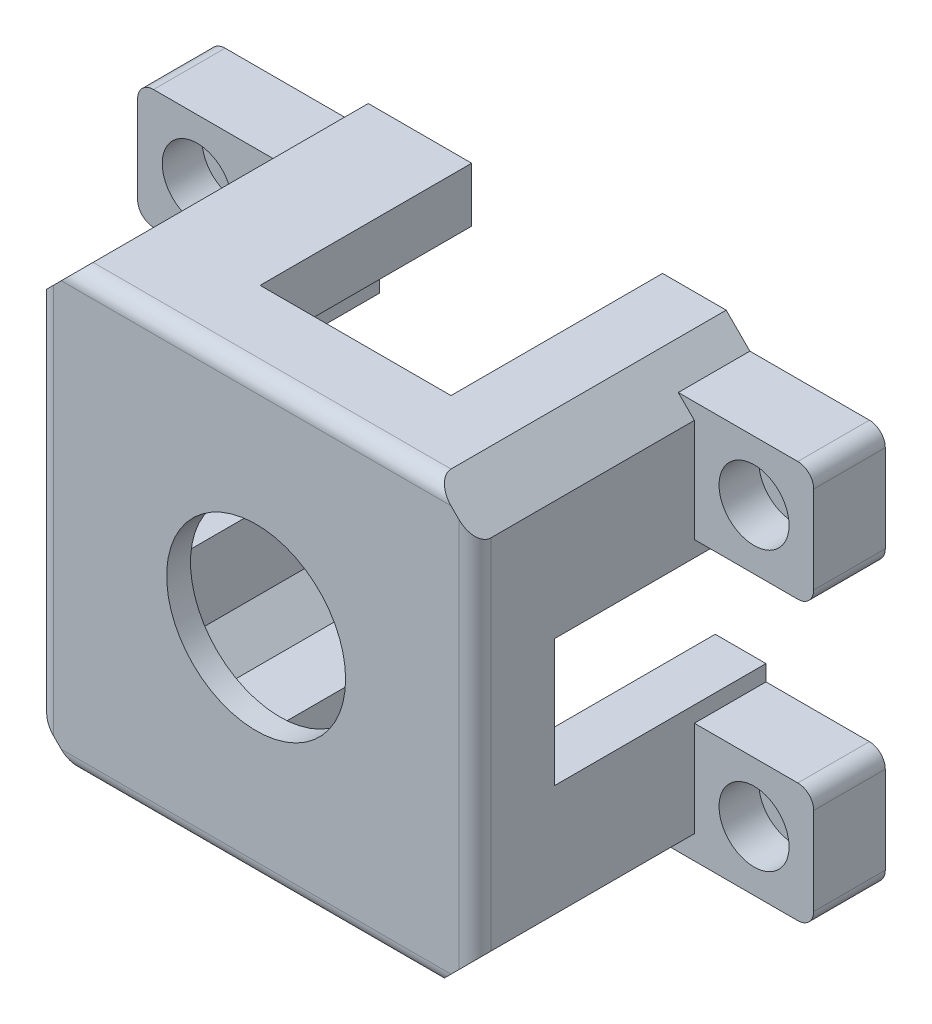
SolidWorks part; units mm, degrees
ref_plane "Front Plane" through (0, 0, 0) normal (0, 0, 1) x (1, 0, 0)
ref_plane "Top Plane" through (0, 0, 0) normal (0, 1, 0) x (1, 0, 0)
ref_plane "Right Plane" through (0, 0, 0) normal (1, 0, 0) x (0, 0, -1)
sketch "Sketch2" plane through (0, 0, 0) normal (0, 0, 1) x (1, 0, 0)
  line L1 (-27.5, -27.0238) -> (27.5, -27.0238)
  line L2 (-27.5, -27.0238) -> (-27.5, 27.9762)
  line L3 (-27.5, 27.9762) -> (27.5, 27.9762)
  line L4 (27.5, -27.0238) -> (27.5, 27.9762)
  line L5 (-27.5, -27.0238) -> (27.5, 27.9762) construction
  line L6 (-27.5, 27.9762) -> (27.5, -27.0238) construction
  line L16 (21.1184, 17.2806) -> (17.2806, 21.1184)
  line L17 (17.2806, 21.1184) -> (-17.2806, 21.1184)
  line L18 (-17.2806, 21.1184) -> (-21.1184, 17.2806)
  line L19 (-21.1184, 17.2806) -> (-21.1184, -17.2806)
  line L20 (-21.1184, -17.2806) -> (-17.2806, -21.1184)
  line L21 (-17.2806, -21.1184) -> (17.2806, -21.1184)
  line L22 (17.2806, -21.1184) -> (21.1184, -17.2806)
  line L23 (21.1184, -17.2806) -> (21.1184, 17.2806)
  circle A2 centre (0, 0.4762) radius 16.593
  dimension "D1" = 55
  dimension "D2" = 55
extrude "Boss-Extrude1" add sketch "Sketch2" along normal blind 33.6 contours L1 L4 L3 L2 L23 L22 L21 L20 L19 L18 L17 L16
sketch "Sketch3" plane through (0, 0, 33.6) normal (0, 0, 1) x (1, 0, 0)
  line L0 (-27.5, 27.9762) -> (27.5, -27.0238)
  line L1 (-27.5, -27.0238) -> (27.5, -27.0238)
  line L2 (-27.5, -27.0238) -> (-27.5, 27.9762)
  line L3 (-27.5, 27.9762) -> (27.5, 27.9762)
  line L4 (27.5, -27.0238) -> (27.5, 27.9762)
  line L5 (27.5, 27.9762) -> (-27.5, -27.0238)
  circle A0 centre (0, 0.4762) radius 11.25
  line M1 (21.1184, 17.2806) -> (21.1184, -17.2806)
  line M2 (21.1184, -17.2806) -> (17.2806, -21.1184)
  line M3 (17.2806, -21.1184) -> (-17.2806, -21.1184)
  line M4 (-17.2806, -21.1184) -> (-21.1184, -17.2806)
  line M5 (-21.1184, -17.2806) -> (-21.1184, 17.2806)
  line M6 (-21.1184, 17.2806) -> (-17.2806, 21.1184)
  line M7 (-17.2806, 21.1184) -> (17.2806, 21.1184)
  line M8 (17.2806, 21.1184) -> (21.1184, 17.2806)
  line M9 (-27.5, -27.0238) -> (27.5, -27.0238)
  line M10 (27.5, -27.0238) -> (27.5, 27.9762)
  line M11 (27.5, 27.9762) -> (-27.5, 27.9762)
  line M12 (-27.5, 27.9762) -> (-27.5, -27.0238)
  dimension "D1" = 22.5
extrude "Boss-Extrude2" add sketch "Sketch3" along normal blind 3 contours A0 L0 L5 M6 M5 M4 | A0 L5 L0 M4 M3 M2 | A0 L0 L5 M2 M1 M8 | A0 L5 L0 M8 M7 M6 | L5 L0 M4 M5 M6 M12 | L5 L0 M4 M9 M2 M3 | L5 L0 M10 M8 M1 M2 | L5 L0 M11 M6 M7 M8
sketch "Sketch4" plane through (0, 0, 0) normal (0, 0, -1) x (-1, 0, 0)
  line L0 (0, 0) -> (-27.5, 0)
  line L1 (-27.5, -27.0238) -> (-27.5, 27.9762) construction
  line L2 (-27.5, 0) -> (-27.5, 10)
  line L3 (0, 0) -> (0, 34.2278) construction
  line L4 (-27.5, 10) -> (-42.5, 10)
  line L5 (-27.5, 10) -> (-27.5, 25)
  line L6 (-27.5, 25) -> (-42.5, 25)
  line L7 (-42.5, 10) -> (-42.5, 25)
  line L8 (42.5, 10) -> (42.5, 25)
  line L9 (27.5, 25) -> (42.5, 25)
  line L10 (27.5, 10) -> (27.5, 25)
  line L11 (27.5, 10) -> (42.5, 10)
  line L16 (-42.5, -10) -> (-42.5, -25)
  line L17 (-27.5, -25) -> (-42.5, -25)
  line L18 (-27.5, -10) -> (-27.5, -25)
  line L19 (-27.5, -10) -> (-42.5, -10)
  line L20 (27.5, -27.0238) -> (-27.5, -27.0238) construction
  line L21 (25, -27.0238) -> (10, -27.0238)
  line L22 (25, -27.0238) -> (25, -42.0238)
  line L23 (25, -42.0238) -> (10, -42.0238)
  line L24 (10, -27.0238) -> (10, -42.0238)
  circle A1 centre (-35, 17.5) radius 2.6
  circle A2 centre (35, 17.5) radius 2.6
  circle A4 centre (-35, -17.5) radius 2.6
  circle A5 centre (17.5, -34.5238) radius 2.6
  point P19 (0, 0)
  point P41 (22.4453, -39.3837)
  dimension "D1" = 10
  dimension "D4" = 5.2
  dimension "D5" = 7.5
  dimension "D10" = 5.2
  dimension "D2" = 15
  dimension "D3" = 15
  dimension "D6" = 7.5
  dimension "D7" = 15
  dimension "D8" = 15
  dimension "D9" = 10
  dimension "D11" = 7.5
  dimension "D12" = 7.5
extrude "Boss-Extrude3" add sketch "Sketch4" against normal blind 9 contours L7 L4 L11 L6 A1 | L11 L19 L16 L17 A4 | A5 | A2 | L22 L23 L24 L21
sketch "Sketch6" plane through (0, 0, 9) normal (0, 0, 1) x (1, 0, 0)
  line L2 (20.13, 0) -> (-20.13, 0) construction
  line L7 (-10, -27.0238) -> (-25, -27.0238)
  line L8 (-25, -27.0238) -> (-25, -42.0238)
  line L9 (-25, -42.0238) -> (-10, -42.0238)
  line L10 (-10, -42.0238) -> (-10, -27.0238)
  line L11 (-10, -27.0238) -> (-25, -27.0238)
  line L12 (-25, -27.0238) -> (-25, -42.0238)
  line L13 (-25, -42.0238) -> (-10, -42.0238)
  line L14 (-10, -42.0238) -> (-10, -27.0238)
  circle A0 centre (35, -17.5) radius 4.4
  circle A2 centre (35, 17.5) radius 4.4
  circle A3 centre (-35, 17.5) radius 4.4
  circle A4 centre (-17.5, -34.5238) radius 4.4
  circle M5 centre (35, -17.5) radius 2.6
  dimension "D1" = 8.8
  dimension "D3" = 8.8
  dimension "D2" = 0
extrude "Cut-Extrude1" cut sketch "Sketch6" against normal blind 5 contours A4 | A3 | A0 M5 | A2
chamfer "Chamfer1" distance 5 angle 45 4 edges at (27.5, -27.0238, 18.3) (-27.5, -27.0238, 18.3) (27.5, 27.9762, 18.3) (-27.5, 27.9762, 18.3)
fillet "Fillet4" radius 2 12 edges at (42.5, -10, 4.5) (42.5, -25, 4.5) (42.5, 10, 4.5) (42.5, 25, 4.5) (-42.5, 10, 4.5) (-42.5, 25, 4.5) (0, -27.0238, 36.6) (-27.5, 0.4762, 36.6) (27.5, 0.4762, 36.6) (0, 27.9762, 36.6) (-25, -42.0238, 4.5) (-10, -42.0238, 4.5)
sketch "Sketch7" plane through (0, -27.0238, 0) normal (0, -1, 0) x (1, 0, 0)
  line L0 (-10, 0) -> (22.5, 0) construction
  line L1 (-9.5, 0) -> (14.5, 0)
  line L2 (-9.5, 0) -> (-9.5, 26.6)
  line L3 (-9.5, 26.6) -> (14.5, 26.6)
  line L4 (14.5, 0) -> (14.5, 26.6)
  line L5 (22.5, 0) -> (22.5, 34.6) construction
  line L6 (-22.5, 34.6) -> (-22.5, 9) construction
  line L7 (22.5, 34.6) -> (-22.5, 34.6) construction
  dimension "D1" = 8
  dimension "D2" = 13
  dimension "D3" = 8
extrude "Cut-Extrude2" cut sketch "Sketch7" against normal blind 67
sketch "Sketch8" plane through (-27.5, 0, 0) normal (-1, 0, 0) x (0, 0, 1)
  line L0 (34.6, -22.0238) -> (34.6, 22.9762) construction
  line L1 (0, 8) -> (26.6, 8)
  line L2 (0, 8) -> (0, -8)
  line L3 (0, -8) -> (26.6, -8)
  line L4 (26.6, 8) -> (26.6, -8)
  point P7 (0, 0)
  dimension "D1" = 8
  dimension "D2" = 16
  dimension "D3" = 26.6
  dimension "D4" = 8
extrude "Cut-Extrude3" cut sketch "Sketch8" against normal blind 67
sketch "Sketch9" plane through (0, 0, 0) normal (0, 0, -1) x (-1, 0, 0)
  line L0 (-21.1184, -17.2806) -> (-21.1184, -8) construction
  line L1 (-21.1184, -8) -> (-27.5, -8) construction
  line L2 (-27.5, -8) -> (-27.5, -10) construction
  line L3 (-27.5, -10) -> (-40.5, -10) construction
  line L4 (-42.5, -12) -> (-42.5, -23) construction
  line L5 (-40.5, -25) -> (-24.5238, -25) construction
  line L6 (-24.5238, -25) -> (-22.5, -27.0238) construction
  line L7 (-22.5, -27.0238) -> (-14.5, -27.0238) construction
  line L8 (-14.5, -27.0238) -> (-14.5, -21.1184) construction
  line L9 (-14.5, -21.1184) -> (-17.2806, -21.1184) construction
  line L10 (-17.2806, -21.1184) -> (-21.1184, -17.2806) construction
  line L11 (27.5, -22.0238) -> (27.5, -8) construction
  line L12 (27.5, -8) -> (21.1184, -8) construction
  line L13 (21.1184, -8) -> (21.1184, -17.2806) construction
  line L14 (21.1184, -17.2806) -> (17.2806, -21.1184) construction
  line L15 (17.2806, -21.1184) -> (9.5, -21.1184) construction
  line L16 (9.5, -21.1184) -> (9.5, -27.0238) construction
  line L17 (9.5, -27.0238) -> (10, -27.0238) construction
  line L18 (10, -27.0238) -> (10, -40.0238) construction
  line L19 (12, -42.0238) -> (23, -42.0238) construction
  line L20 (25, -40.0238) -> (25, -24.5238) construction
  line L21 (25, -24.5238) -> (27.5, -22.0238) construction
  line L22 (21.1184, 17.2806) -> (21.1184, 8) construction
  line L23 (21.1184, 8) -> (27.5, 8) construction
  line L24 (27.5, 8) -> (27.5, 10) construction
  line L25 (27.5, 10) -> (40.5, 10) construction
  line L26 (42.5, 12) -> (42.5, 23) construction
  line L27 (40.5, 25) -> (25.4762, 25) construction
  line L28 (25.4762, 25) -> (22.5, 27.9762) construction
  line L29 (22.5, 27.9762) -> (9.5, 27.9762) construction
  line L30 (9.5, 27.9762) -> (9.5, 21.1184) construction
  line L31 (9.5, 21.1184) -> (17.2806, 21.1184) construction
  line L32 (17.2806, 21.1184) -> (21.1184, 17.2806) construction
  line L33 (-27.5, 10) -> (-27.5, 8) construction
  line L34 (-27.5, 8) -> (-21.1184, 8) construction
  line L35 (-21.1184, 8) -> (-21.1184, 17.2806) construction
  line L36 (-21.1184, 17.2806) -> (-17.2806, 21.1184) construction
  line L37 (-17.2806, 21.1184) -> (-14.5, 21.1184) construction
  line L38 (-14.5, 21.1184) -> (-14.5, 27.9762) construction
  line L39 (-14.5, 27.9762) -> (-22.5, 27.9762) construction
  line L40 (-22.5, 27.9762) -> (-25.4762, 25) construction
  line L41 (-25.4762, 25) -> (-40.5, 25) construction
  line L42 (-42.5, 23) -> (-42.5, 12) construction
  line L43 (-40.5, 10) -> (-27.5, 10) construction
  line L44 (-21.1184, -17.2806) -> (-21.1184, -8)
  line L45 (-21.1184, -8) -> (-27.5, -8)
  line L46 (-27.5, -8) -> (-27.5, -10)
  line L47 (-27.5, -10) -> (-40.5, -10)
  line L48 (-42.5, -12) -> (-42.5, -23)
  line L49 (-40.5, -25) -> (-24.5238, -25)
  line L50 (-24.5238, -25) -> (-22.5, -27.0238)
  line L51 (-22.5, -27.0238) -> (-14.5, -27.0238)
  line L52 (-14.5, -27.0238) -> (-14.5, -21.1184)
  line L53 (-14.5, -21.1184) -> (-17.2806, -21.1184)
  line L54 (-17.2806, -21.1184) -> (-21.1184, -17.2806)
  line L55 (27.5, -22.0238) -> (27.5, -8)
  line L56 (27.5, -8) -> (21.1184, -8)
  line L57 (21.1184, -8) -> (21.1184, -17.2806)
  line L58 (21.1184, -17.2806) -> (17.2806, -21.1184)
  line L59 (17.2806, -21.1184) -> (9.5, -21.1184)
  line L60 (9.5, -21.1184) -> (9.5, -27.0238)
  line L61 (9.5, -27.0238) -> (10, -27.0238)
  line L62 (10, -27.0238) -> (10, -40.0238)
  line L63 (12, -42.0238) -> (23, -42.0238)
  line L64 (25, -40.0238) -> (25, -24.5238)
  line L65 (25, -24.5238) -> (27.5, -22.0238)
  line L66 (21.1184, 17.2806) -> (21.1184, 8)
  line L67 (21.1184, 8) -> (27.5, 8)
  line L68 (27.5, 8) -> (27.5, 10)
  line L69 (27.5, 10) -> (40.5, 10)
  line L70 (42.5, 12) -> (42.5, 23)
  line L71 (40.5, 25) -> (25.4762, 25)
  line L72 (25.4762, 25) -> (22.5, 27.9762)
  line L73 (22.5, 27.9762) -> (9.5, 27.9762)
  line L74 (9.5, 27.9762) -> (9.5, 21.1184)
  line L75 (9.5, 21.1184) -> (17.2806, 21.1184)
  line L76 (17.2806, 21.1184) -> (21.1184, 17.2806)
  line L77 (-27.5, 10) -> (-27.5, 8)
  line L78 (-27.5, 8) -> (-21.1184, 8)
  line L79 (-21.1184, 8) -> (-21.1184, 17.2806)
  line L80 (-21.1184, 17.2806) -> (-17.2806, 21.1184)
  line L81 (-17.2806, 21.1184) -> (-14.5, 21.1184)
  line L82 (-14.5, 21.1184) -> (-14.5, 27.9762)
  line L83 (-14.5, 27.9762) -> (-22.5, 27.9762)
  line L84 (-22.5, 27.9762) -> (-25.4762, 25)
  line L85 (-25.4762, 25) -> (-40.5, 25)
  line L86 (-42.5, 23) -> (-42.5, 12)
  line L87 (-40.5, 10) -> (-27.5, 10)
  arc A0 (-40.5, -10) -> (-42.5, -12) centre (-40.5, -12) ccw construction
  arc A1 (-42.5, -23) -> (-40.5, -25) centre (-40.5, -23) ccw construction
  arc A2 (10, -40.0238) -> (12, -42.0238) centre (12, -40.0238) ccw construction
  arc A3 (23, -42.0238) -> (25, -40.0238) centre (23, -40.0238) ccw construction
  arc A4 (40.5, 10) -> (42.5, 12) centre (40.5, 12) ccw construction
  arc A5 (42.5, 23) -> (40.5, 25) centre (40.5, 23) ccw construction
  arc A6 (-40.5, 25) -> (-42.5, 23) centre (-40.5, 23) ccw construction
  arc A7 (-42.5, 12) -> (-40.5, 10) centre (-40.5, 12) ccw construction
  arc A8 (-40.5, -10) -> (-42.5, -12) centre (-40.5, -12) ccw
  arc A9 (-42.5, -23) -> (-40.5, -25) centre (-40.5, -23) ccw
  arc A10 (10, -40.0238) -> (12, -42.0238) centre (12, -40.0238) ccw
  arc A11 (23, -42.0238) -> (25, -40.0238) centre (23, -40.0238) ccw
  arc A12 (40.5, 10) -> (42.5, 12) centre (40.5, 12) ccw
  arc A13 (42.5, 23) -> (40.5, 25) centre (40.5, 23) ccw
  arc A14 (-40.5, 25) -> (-42.5, 23) centre (-40.5, 23) ccw
  arc A15 (-42.5, 12) -> (-40.5, 10) centre (-40.5, 12) ccw
